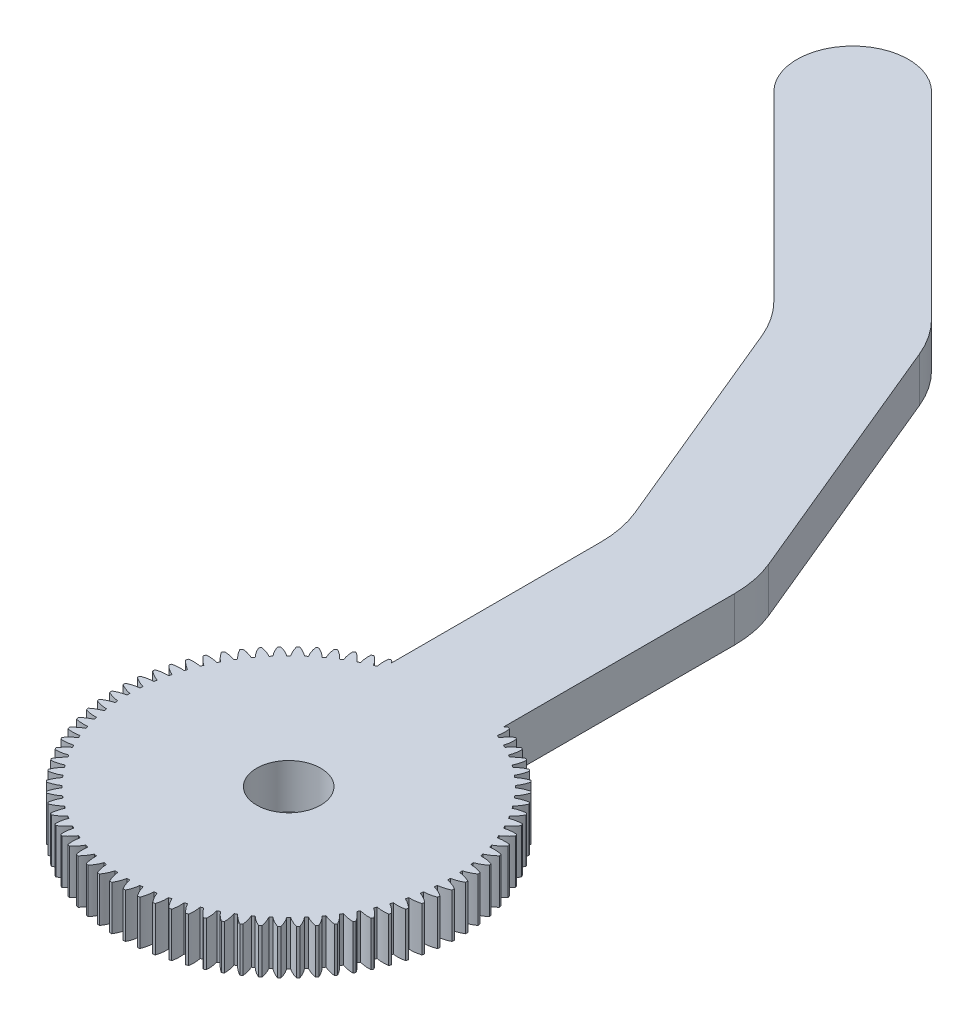
SolidWorks part; units mm, degrees
ref_plane "Front Plane" through (0, 0, 0) normal (0, 0, 1) x (1, 0, 0)
ref_plane "Top Plane" through (0, 0, 0) normal (0, 1, 0) x (1, 0, 0)
ref_plane "Right Plane" through (0, 0, 0) normal (1, 0, 0) x (0, 0, -1)
sketch "Sketch1" plane through (0, 0, 0) normal (0, 1, 0) x (1, 0, 0)
  circle A0 centre (0, 0) radius 15.375
  circle A2 centre (0, 0) radius 2.875
  dimension "D1" = 30.75
  dimension "D3" = 5.75
extrude "Boss-Extrude1" add sketch "Sketch1" along normal blind 4
sketch "Sketch2" plane through (0, 4, 0) normal (0, 1, 0) x (1, 0, 0)
  line L0 (0, 0) -> (0, 15.375) construction
  circle A0 centre (0, 0) radius 14.375
  circle A1 centre (0, 0) radius 15.375 construction
  arc A2 (0.125, 14.3745) -> (0.5, 15.3669) centre (3.0746, 13.8269) cw
  arc A3 (-0.125, 14.3745) -> (-0.5, 15.3669) centre (-3.0746, 13.8269) ccw
  circle M3 centre (0, 0) radius 15.375
  dimension "D1" = 1
  dimension "D4" = 3
  dimension "D2" = 0.125
  dimension "D3" = 0.5
extrude "Cut-Extrude1" cut sketch "Sketch2" along direction (0, 1, 0) on the side against the normal through all contours L0 A0 A2 M3 | A0 L0 A3 M3
pattern_circular "CirPattern1" count 80 over 360 about axis through (0, 0, 0) along (0, 1, 0) of "Cut-Extrude1"
sketch "Sketch3" plane through (0, 4, 0) normal (0, 1, 0) x (1, 0, 0)
  line L5 (5, 10) -> (-5, 10)
  line L6 (0, 0) -> (0, 10) construction
  line L7 (-5, 10) -> (-5, 33.0109)
  line L9 (-5.7612, 36.8377) -> (-13.8059, 56.2593)
  line L10 (-15.9736, 59.5035) -> (-32.2448, 75.7747)
  line L11 (-25.1737, 82.8457) -> (-7.496, 65.1681)
  line L12 (-5.3283, 61.9238) -> (4.2388, 38.8268)
  line L13 (5, 35) -> (5, 10)
  arc A0 (-32.2448, 75.7747) -> (-25.1737, 82.8457) centre (-28.7092, 79.3102) cw
  arc A1 (-5, 33.0109) -> (-5.7612, 36.8377) centre (-15, 33.0109) ccw
  arc A2 (4.2388, 38.8268) -> (5, 35) centre (-5, 35) cw
  arc A3 (-7.496, 65.1681) -> (-5.3283, 61.9238) centre (-14.5671, 58.097) cw
  arc A4 (-13.8059, 56.2593) -> (-15.9736, 59.5035) centre (-23.0447, 52.4324) ccw
  point P10 (-7.269, 64.7369)
  point P13 (-25.6448, 82.6449)
  point P16 (-5, 35)
  point P23 (-14.5671, 58.097)
  dimension "D10" = 10
  dimension "D1" = 10
  dimension "D2" = 10
  dimension "D3" = 10
  dimension "D4" = 25
  dimension "D5" = 10
  dimension "D6" = 25
  dimension "D7" = 25
  dimension "D8" = 135
  dimension "D9" = 157.5
extrude "Boss-Extrude2" add sketch "Sketch3" against normal blind 4
